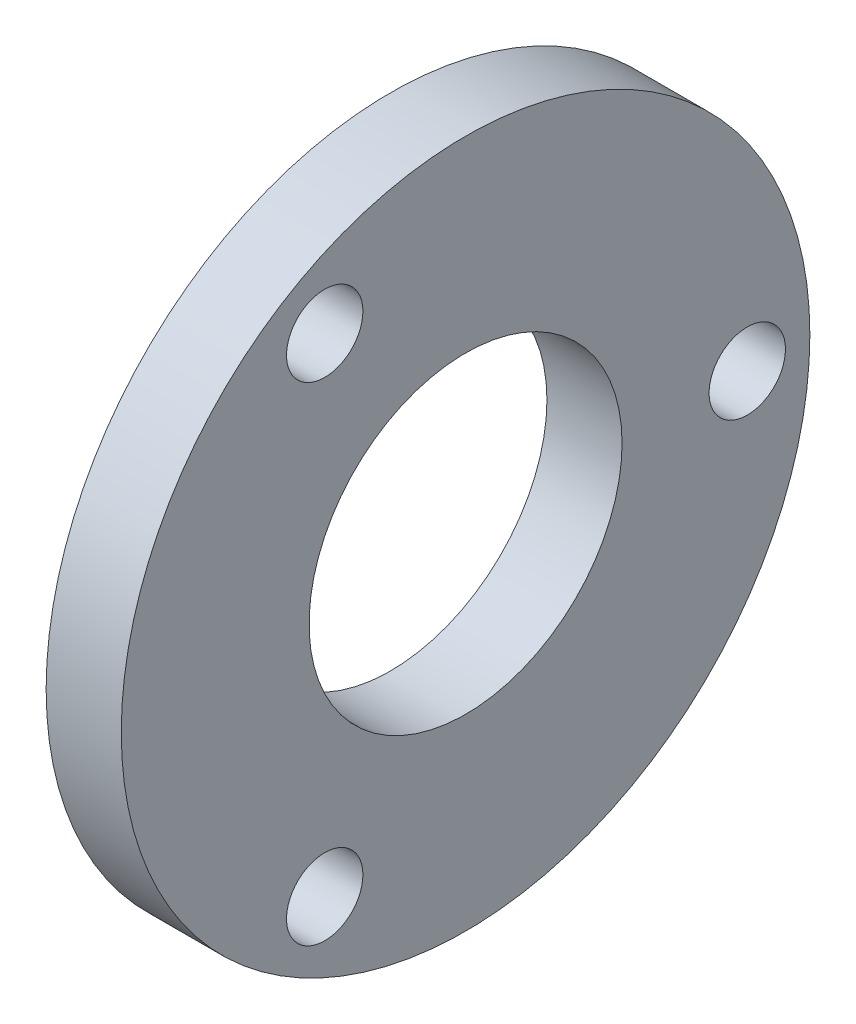
SolidWorks part; units mm, degrees
material "ABS"
ref_plane "前视基准面" through (0, 0, 0) normal (0, 0, 1) x (1, 0, 0)
ref_plane "上视基准面" through (0, 0, 0) normal (0, 1, 0) x (1, 0, 0)
ref_plane "右视基准面" through (0, 0, 0) normal (1, 0, 0) x (0, 0, -1)
sketch "草图1" plane through (0, 0, 0) normal (1, 0, 0) x (0, 0, -1)
  circle A0 centre (0, 0) radius 27.5
  circle A1 centre (0, 0) radius 12.5
  circle A2 centre (0, 0) radius 22.5 construction
  circle A3 centre (22.5, 0) radius 3.05
  circle A4 centre (-11.25, -19.4856) radius 3.05
  circle A5 centre (-11.25, 19.4856) radius 3.05
  point P19 (0, 0)
  dimension "D1" = 55
  dimension "D2" = 25
  dimension "D3" = 45
  dimension "D4" = 6.1
  dimension "D5" = 3
extrude "凸台-拉伸1" add sketch "草图1" along normal blind 6
